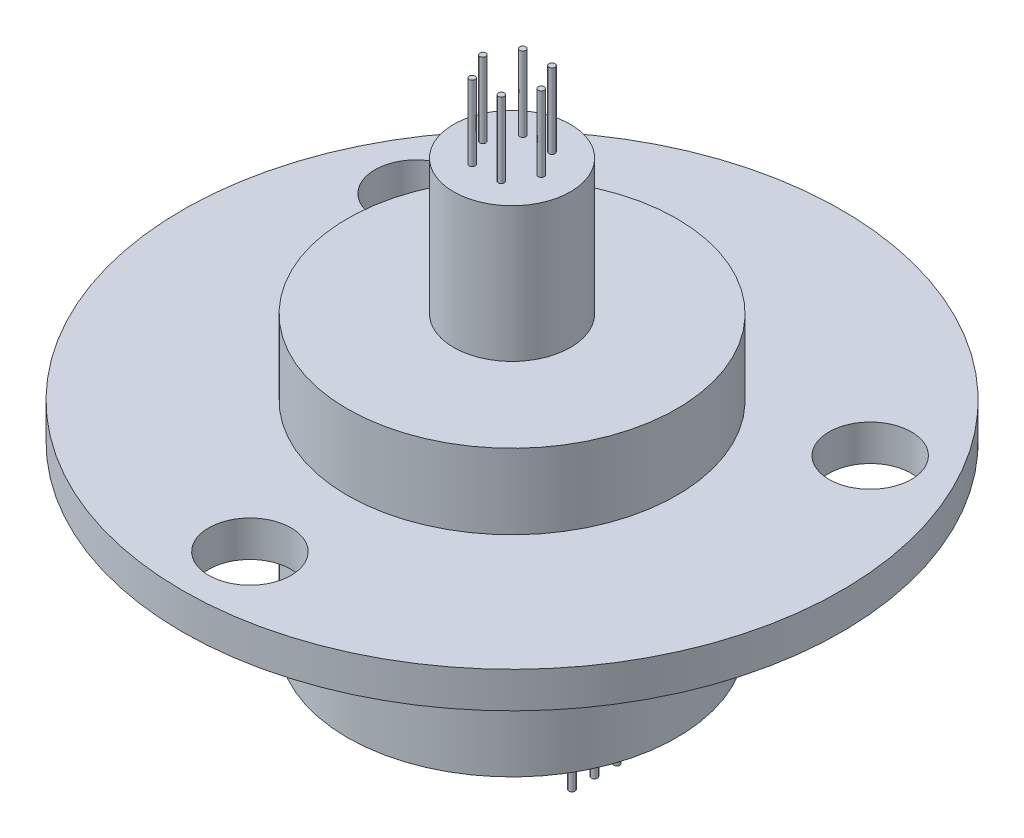
SolidWorks part; units mm, degrees
ref_plane "Alzado" through (0, 0, 0) normal (0, 0, 1) x (1, 0, 0)
ref_plane "Planta" through (0, 0, 0) normal (0, 1, 0) x (1, 0, 0)
ref_plane "Vista lateral" through (0, 0, 0) normal (1, 0, 0) x (0, 0, -1)
sketch "Croquis1" plane through (0, 0, 0) normal (0, 1, 0) x (1, 0, 0)
  line L0 (0, 0) -> (17.5, 0) construction
  line L1 (0, 0) -> (15.1554, 8.75) construction
  circle A0 centre (0, 0) radius 22
  circle A1 centre (0, 0) radius 17.5 construction
  circle A2 centre (15.1554, 8.75) radius 2.75
  circle A3 centre (0, -17.5) radius 2.75
  circle A4 centre (-15.1554, 8.75) radius 2.75
  point P14 (0, 0)
  dimension "D1" = 44
  dimension "D2" = 35
  dimension "D4" = 5.5
  dimension "D3" = 30
  dimension "D5" = 3
extrude "Saliente-Extruir1" add sketch "Croquis1" along normal mid plane 2.4
sketch "Croquis3" plane through (0, 1.2, 0) normal (0, 1, 0) x (1, 0, 0)
  circle A0 centre (0, 0) radius 11
  dimension "D1" = 22
extrude "Saliente-Extruir2" add sketch "Croquis3" along normal blind 5
sketch "Croquis4" plane through (0, 6.2, 0) normal (0, 1, 0) x (1, 0, 0)
  circle A0 centre (0, 0) radius 3.9
  dimension "D1" = 7.8
extrude "Saliente-Extruir3" add sketch "Croquis4" along normal blind 9
sketch "Croquis5" plane through (0, -1.2, 0) normal (0, -1, 0) x (1, 0, 0)
  circle A0 centre (0, 0) radius 11
  dimension "D1" = 22
extrude "Saliente-Extruir4" add sketch "Croquis5" along normal blind 11.6
sketch "Croquis6" plane through (0, 15.2, 0) normal (0, 1, 0) x (1, 0, 0)
  line L0 (0, 0) -> (3.9, 0) construction
  circle A0 centre (0, 0) radius 3.9 construction
  circle A1 centre (0, 0) radius 3.9 construction
  circle A2 centre (1.95, 0) radius 0.2025
  circle A3 centre (0.975, -1.6887) radius 0.2025
  circle A4 centre (-0.975, -1.6887) radius 0.2025
  circle A5 centre (-1.95, 0) radius 0.2025
  circle A6 centre (-0.975, 1.6887) radius 0.2025
  circle A7 centre (0.975, 1.6887) radius 0.2025
  point P21 (0, 0)
  dimension "D1" = 0.405
  dimension "D2" = 6
extrude "Saliente-Extruir5" add sketch "Croquis6" along normal blind 5 separate body
sketch "Croquis7" plane through (0, -12.8, 0) normal (0, -1, 0) x (1, 0, 0)
  line L0 (0, 0) -> (0, 6.9966) construction
  line L1 (0, 0) -> (11, 0) construction
  line L2 (5.5, 0) -> (5.5, 1.5) construction
  line L3 (5.5, 0) -> (5.5, -1.5) construction
  circle A0 centre (0, 0) radius 11 construction
  circle A1 centre (5.5, 0) radius 0.2025
  circle A2 centre (5.5, 1.5) radius 0.2025
  circle A3 centre (5.5, -1.5) radius 0.2025
  circle A4 centre (-5.5, -1.5) radius 0.2025
  circle A5 centre (-5.5, 0) radius 0.2025
  circle A6 centre (-5.5, 1.5) radius 0.2025
  dimension "D1" = 0.405
  dimension "D2" = 0.405
  dimension "D3" = 0.405
  dimension "D4" = 1.5
  dimension "D5" = 1.5
extrude "Saliente-Extruir6" add sketch "Croquis7" along normal blind 5
